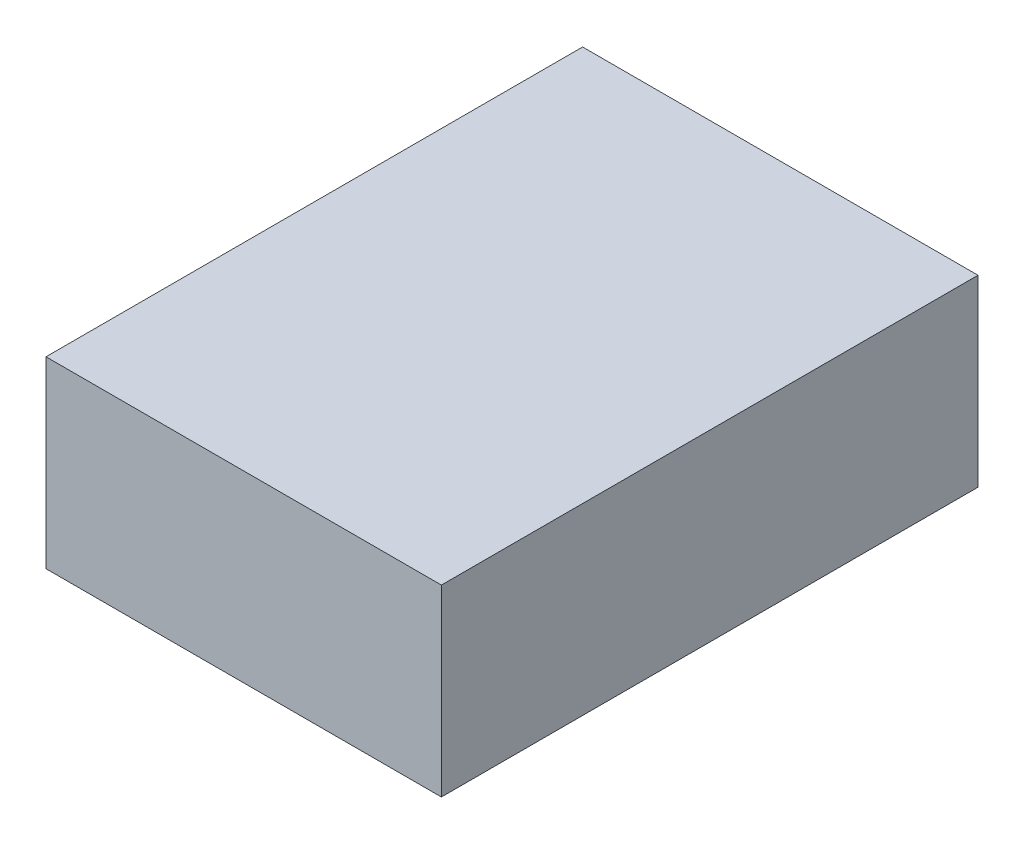
SolidWorks part; units mm, degrees
ref_plane "Front Plane" through (0, 0, 0) normal (0, 0, 1) x (1, 0, 0)
ref_plane "Top Plane" through (0, 0, 0) normal (0, 1, 0) x (1, 0, 0)
ref_plane "Right Plane" through (0, 0, 0) normal (1, 0, 0) x (0, 0, -1)
sketch "Sketch1" plane through (0, 0, 0) normal (0, 1, 0) x (1, 0, 0)
  line L1 (-88.9, -120.65) -> (88.9, -120.65)
  line L2 (-88.9, -120.65) -> (-88.9, 120.65)
  line L3 (-88.9, 120.65) -> (88.9, 120.65)
  line L4 (88.9, -120.65) -> (88.9, 120.65)
  line L5 (-88.9, -120.65) -> (88.9, 120.65) construction
  line L6 (-88.9, 120.65) -> (88.9, -120.65) construction
  point P0 (0, 0)
  dimension "D1" = 177.8
  dimension "D2" = 241.3
extrude "Boss-Extrude1" add sketch "Sketch1" along normal blind 82.55
